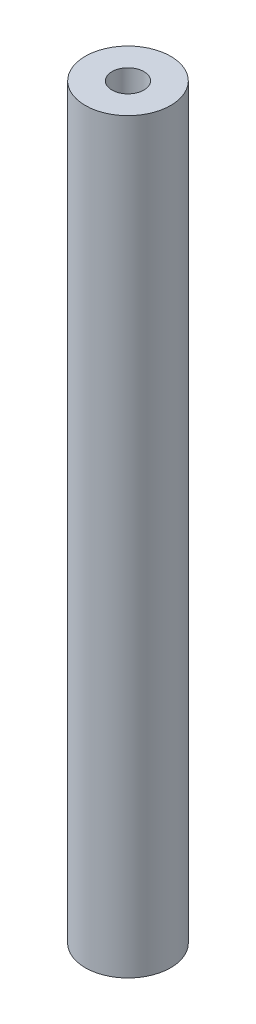
SolidWorks part; units mm, degrees
ref_plane "前视基准面" through (0, 0, 0) normal (0, 0, 1) x (1, 0, 0)
ref_plane "上视基准面" through (0, 0, 0) normal (0, 1, 0) x (1, 0, 0)
ref_plane "右视基准面" through (0, 0, 0) normal (1, 0, 0) x (0, 0, -1)
sketch "草图1" plane through (0, 0, 0) normal (0, 1, 0) x (1, 0, 0)
  circle A0 centre (-1.9321, 1.4107) radius 2
  circle A1 centre (-1.9321, 1.4107) radius 0.75
  dimension "D1" = 4
  dimension "D2" = 1.5
extrude "凸台-拉伸1" add sketch "草图1" along normal blind 35
